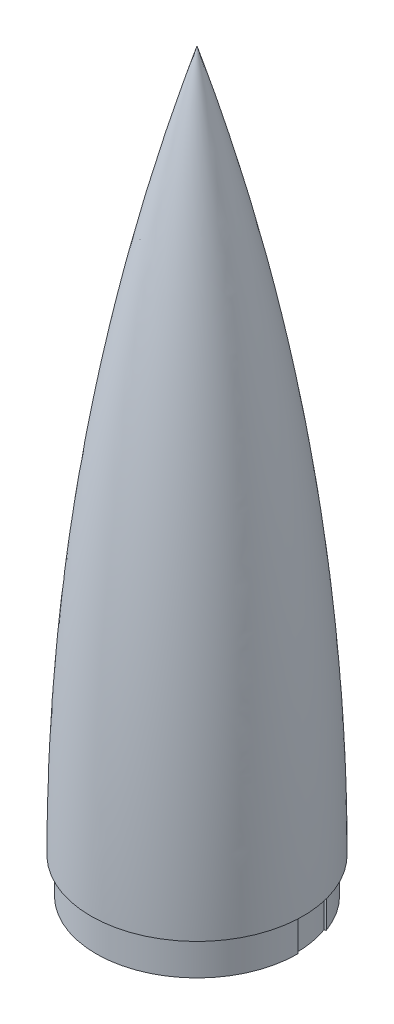
SolidWorks part; units mm, degrees
ref_plane "Front Plane" through (0, 0, 0) normal (0, 0, 1) x (1, 0, 0)
ref_plane "Top Plane" through (0, 0, 0) normal (0, 1, 0) x (1, 0, 0)
ref_plane "Right Plane" through (0, 0, 0) normal (1, 0, 0) x (0, 0, -1)
sketch "Sketch1" plane through (0, 0, 0) normal (0, 1, 0) x (1, 0, 0)
  circle A0 centre (0, 0) radius 57
extrude "Boss-Extrude1" add sketch "Sketch1" along normal blind 20
sketch "Sketch2" plane through (0, 20, 0) normal (0, 1, 0) x (1, 0, 0)
  line L0 (-57, 0) -> (-56, 0)
  line L1 (52.6228, 19.1531) -> (53.5625, 19.4951)
  line L2 (-52.6228, -19.1531) -> (-53.5625, -19.4951)
  line L3 (56, 0) -> (57, 0)
  circle A0 centre (0, 0) radius 57 construction
  arc A2 (56, 0) -> (52.6228, 19.1531) centre (0, 0) ccw
  circle A3 centre (0, 0) radius 56
  arc A4 (-56, 0) -> (-52.6228, -19.1531) centre (0, 0) ccw
  arc A5 (-57, 0) -> (-53.5625, -19.4951) centre (0, 0) ccw
  arc A6 (57, 0) -> (53.5625, 19.4951) centre (0, 0) ccw
  dimension "D1" = 20
  dimension "D2" = 20
  dimension "D3" = 1
extrude "Cut-Extrude1" cut sketch "Sketch2" against normal blind 20
sketch "Sketch3" plane through (0, 0, 0) normal (0, 0, 1) x (1, 0, 0)
  line L0 (0, 0) -> (0, 20)
  line L1 (0, 20) -> (60, 20)
  line L2 (0, 415.9183) -> (0, 20)
  arc A0 (60, 20) -> (0, 415.9183) centre (-1276.2611, 20) ccw
revolve "Revolve1" add sketch "Sketch3" angle 360 about L2
